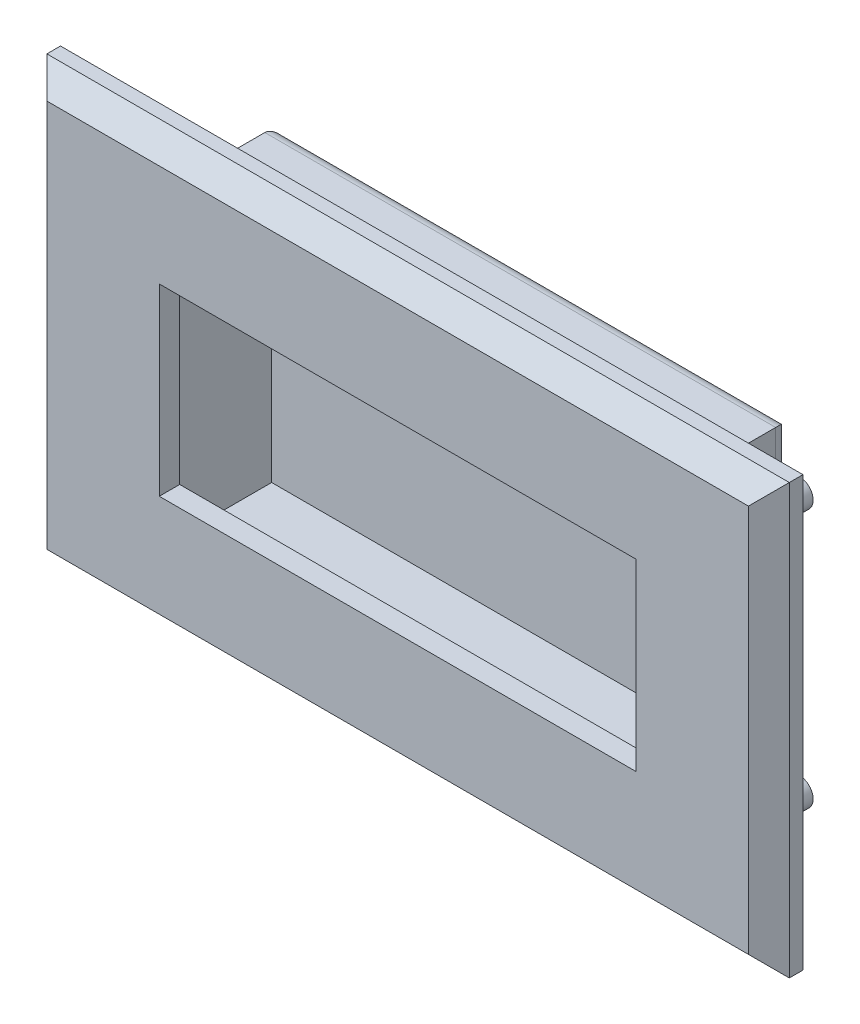
SolidWorks part; units mm, degrees
ref_plane "前视基准面" through (0, 0, 0) normal (0, 0, 1) x (1, 0, 0)
ref_plane "上视基准面" through (0, 0, 0) normal (0, 1, 0) x (1, 0, 0)
ref_plane "右视基准面" through (0, 0, 0) normal (1, 0, 0) x (0, 0, -1)
sketch "草图1" plane through (0, 0, 0) normal (0, 0, 1) x (1, 0, 0)
  line L1 (-54.5, -31.5) -> (54.5, -31.5)
  line L2 (-54.5, -31.5) -> (-54.5, 31.5)
  line L3 (-54.5, 31.5) -> (54.5, 31.5)
  line L4 (54.5, -31.5) -> (54.5, 31.5)
  line L5 (-54.5, -31.5) -> (54.5, 31.5) construction
  line L6 (-54.5, 31.5) -> (54.5, -31.5) construction
  point P0 (0, 0)
  dimension "D1" = 109
  dimension "D2" = 63
extrude "凸台-拉伸1" add sketch "草图1" along normal blind 5
chamfer "倒角1" distance 3 angle 45 4 edges at (54.5, 0, 5) (0, -31.5, 5) (-54.5, 0, 5) (0, 31.5, 5)
sketch "草图2" plane through (0, 0, 5) normal (0, 0, 1) x (1, 0, 0)
  line L1 (-37.5, -22.5) -> (37.5, -22.5)
  line L2 (-37.5, -22.5) -> (-37.5, 22.5)
  line L3 (-37.5, 22.5) -> (37.5, 22.5)
  line L4 (37.5, -22.5) -> (37.5, 22.5)
  line L5 (-37.5, -22.5) -> (37.5, 22.5) construction
  line L6 (-37.5, 22.5) -> (37.5, -22.5) construction
  point P0 (0, 0)
  dimension "D1" = 75
  dimension "D2" = 45
extrude "凸台-拉伸2" add sketch "草图2" against normal blind 20
sketch "草图3" plane through (0, 0, 5) normal (0, 0, 1) x (1, 0, 0)
  line L1 (-35, -13.5) -> (35, -13.5)
  line L2 (-35, -13.5) -> (-35, 13.5)
  line L3 (-35, 13.5) -> (35, 13.5)
  line L4 (35, -13.5) -> (35, 13.5)
  line L5 (-35, -13.5) -> (35, 13.5) construction
  line L6 (-35, 13.5) -> (35, -13.5) construction
  point P0 (0, 0)
  dimension "D1" = 70
  dimension "D2" = 27
extrude "切除-拉伸1" cut sketch "草图3" against normal blind 18
sketch "草图4" plane through (0, 0, -13) normal (0, 0, 1) x (1, 0, 0)
  line L0 (-37.5, 22.5) -> (37.5, 22.5) construction
  line L1 (-36.5, -21.5) -> (36.5, -21.5)
  line L2 (-36.5, -21.5) -> (-36.5, 21.5)
  line L3 (-36.5, 21.5) -> (36.5, 21.5)
  line L4 (36.5, -21.5) -> (36.5, 21.5)
  line L5 (-36.5, -21.5) -> (36.5, 21.5) construction
  line L6 (-36.5, 21.5) -> (36.5, -21.5) construction
  line L7 (37.5, 22.5) -> (37.5, -22.5) construction
  point P0 (0, 0)
  dimension "D1" = 1
  dimension "D2" = 1
extrude "切除-拉伸2" cut sketch "草图4" along normal blind 15
sketch "草图5" plane through (0, 0, 0) normal (0, 0, -1) x (-1, 0, 0)
  line L1 (-44, -19) -> (44, -19) construction
  line L2 (-44, -19) -> (-44, 19) construction
  line L3 (-44, 19) -> (44, 19) construction
  line L4 (44, -19) -> (44, 19) construction
  line L5 (-44, -19) -> (44, 19) construction
  line L6 (-44, 19) -> (44, -19) construction
  circle A0 centre (44, 19) radius 2
  circle A1 centre (44, -19) radius 2
  circle A2 centre (-44, -19) radius 2
  circle A3 centre (-44, 19) radius 2
  point P0 (0, 0)
  dimension "D1" = 4
  dimension "D2" = 88
  dimension "D3" = 38
extrude "凸台-拉伸3" add sketch "草图5" along normal blind 10
fillet "圆角1" radius 2 4 edges at (37.5, 0, -15) (0, 22.5, -15) (-37.5, 0, -15) (0, -22.5, -15)
